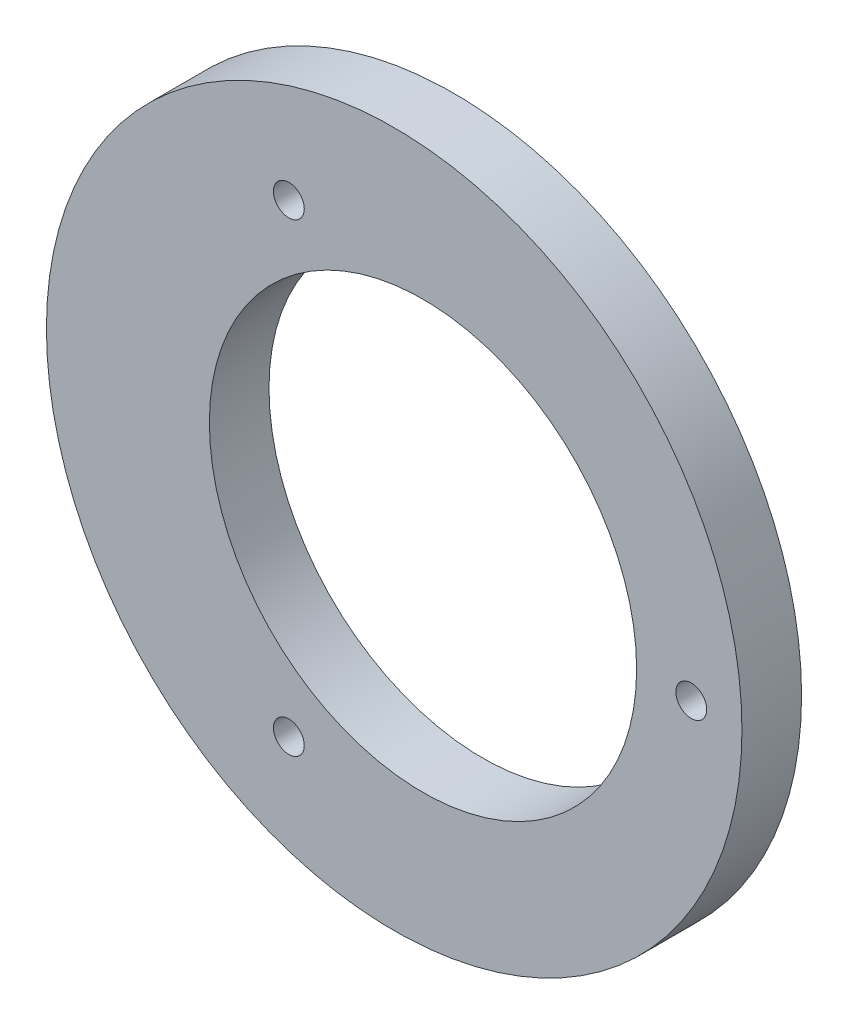
SolidWorks part; units mm, degrees
ref_plane "Płaszczyzna przednia" through (0, 0, 0) normal (0, 0, 1) x (1, 0, 0)
ref_plane "Płaszczyzna górna" through (0, 0, 0) normal (0, 1, 0) x (1, 0, 0)
ref_plane "Płaszczyzna prawa" through (0, 0, 0) normal (1, 0, 0) x (0, 0, -1)
sketch "Szkic1" plane through (0, 0, 0) normal (0, 0, 1) x (1, 0, 0)
  circle A0 centre (41.7198, 20.3847) radius 35
  dimension "D1" = 70
extrude "Dodanie-wyciągnięcie1" add sketch "Szkic1" along normal blind 6
sketch "Szkic2" plane through (0, 0, 0) normal (0, 0, 1) x (1, 0, 0)
  line L0 (76.7198, 20.3847) -> (11.0273, 20.3847) construction
  circle A0 centre (41.7198, 20.3847) radius 35 construction
  point P5 (41.7198, 20.3847)
  point P6 (35.1303, 29.0461)
sketch "Szkic3" plane through (0, 0, 6) normal (0, 0, 1) x (1, 0, 0)
  line L0 (76.7198, 20.3847) -> (11.0273, 20.3847) construction
  circle A0 centre (44.6198, 20.3847) radius 21.5
  circle A1 centre (44.6198, 20.3847) radius 21.25 construction
  dimension "D2" = 0
  dimension "D3" = 43
  dimension "D1" = 0
extrude "Wytnij-wyciągnięcie1" cut sketch "Szkic3" against normal blind 6
sketch "Szkic4" plane through (0, 0, 6) normal (0, 0, 1) x (1, 0, 0)
  circle A0 centre (31.1198, -2.998) radius 1.55 construction
  circle A4 centre (71.6198, 20.3847) radius 1.55 construction
  circle A5 centre (31.1198, -2.998) radius 1.55
  circle A6 centre (71.6198, 20.3847) radius 1.55
  circle A7 centre (31.1198, 43.7674) radius 1.55 construction
  circle A8 centre (31.1198, 43.7674) radius 1.55
extrude "Wytnij-wyciągnięcie2" cut sketch "Szkic4" against normal blind 6
